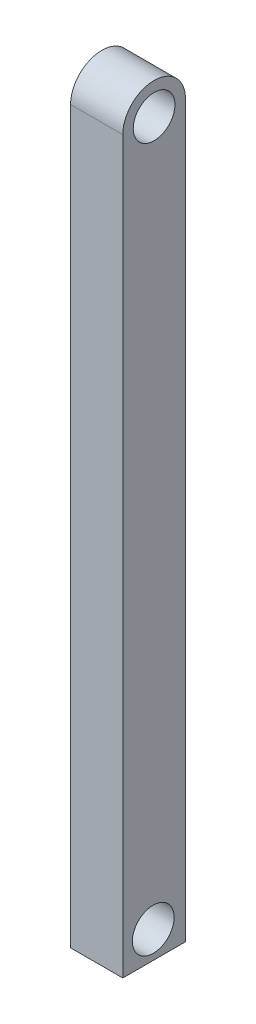
SolidWorks part; units mm, degrees
ref_plane "Alzado" through (0, 0, 0) normal (0, 0, 1) x (1, 0, 0)
ref_plane "Planta" through (0, 0, 0) normal (0, 1, 0) x (1, 0, 0)
ref_plane "Vista lateral" through (0, 0, 0) normal (1, 0, 0) x (0, 0, -1)
sketch "Croquis1" plane through (0, 0, 0) normal (0, 0, 1) x (1, 0, 0)
  line L1 (-8.5078, 72.4285) -> (-6.0078, 72.4285)
  line L2 (-6.0078, 72.4285) -> (-6.0078, 35.4285)
  line L3 (-6.0078, 35.4285) -> (-8.5078, 35.4285)
  line L5 (-8.5078, 72.4285) -> (-8.5078, 35.4285)
  dimension "D1" = 2.5
  dimension "D2" = 37
extrude "Saliente-Extruir1" add sketch "Croquis1" along normal blind 3
sketch "Croquis10" plane through (-6.0078, 0, 0) normal (1, 0, 0) x (0, 0, -1)
  line L0 (-3, 72.4285) -> (0, 72.4285) construction
  line L6 (-3, 35.4285) -> (-3, 72.4285) construction
  line L7 (0, 35.4285) -> (0, 72.4285) construction
  line L8 (-3, 70.4021) -> (-3, 72.4285)
  line L9 (-3, 72.4285) -> (0, 72.4285)
  line L10 (0, 72.4285) -> (0, 70.4021)
  circle A0 centre (-1.5, 70.4021) radius 1
  arc A1 (-3, 70.4021) -> (0, 70.4021) centre (-1.5, 70.4021) cw
  point P8 (-1.5, 72.4285)
  dimension "D1" = 2
extrude "Cortar-Extruir7" cut sketch "Croquis10" against normal up to next
sketch "Croquis12" plane through (-6.0078, 0, 0) normal (1, 0, 0) x (0, 0, -1)
  circle A0 centre (-1.5411, 36.7221) radius 1
  dimension "D1" = 2
extrude "Cortar-Extruir9" cut sketch "Croquis12" against normal blind 10
